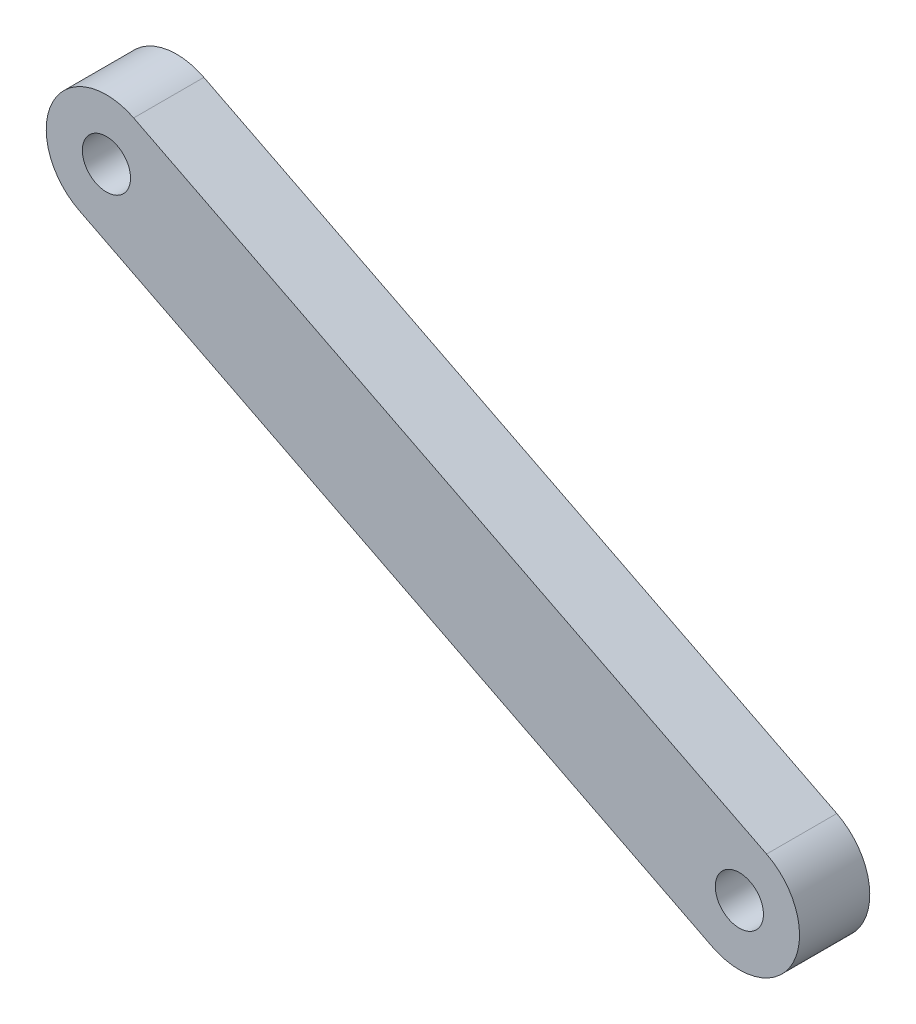
SolidWorks part; units mm, degrees
ref_plane "Front Plane" through (0, 0, 0) normal (0, 0, 1) x (1, 0, 0)
ref_plane "Top Plane" through (0, 0, 0) normal (0, 1, 0) x (1, 0, 0)
ref_plane "Right Plane" through (0, 0, 0) normal (1, 0, 0) x (0, 0, -1)
sketch "Sketch16" plane through (0, 0, 0) normal (0, 0, 1) x (1, 0, 0)
  line B0 (-135.7084, -267.5504) -> (3018.6655, -1867.5295)
  line B1 (135.7084, 267.5504) -> (3290.0824, -1332.4286)
  arc B2 (135.7084, 267.5504) -> (-135.7084, -267.5504) centre (0, 0) ccw
  arc B3 (3018.6655, -1867.5295) -> (3290.0824, -1332.4286) centre (3154.374, -1599.9791) ccw
  circle B4 centre (0, 0) radius 120
  circle B5 centre (3154.374, -1599.9791) radius 120
sketch_block_instance "Block13-1"
sketch_block "Block13"
extrude "Boss-Extrude13" add sketch "Sketch16" along normal blind 350 separate body
